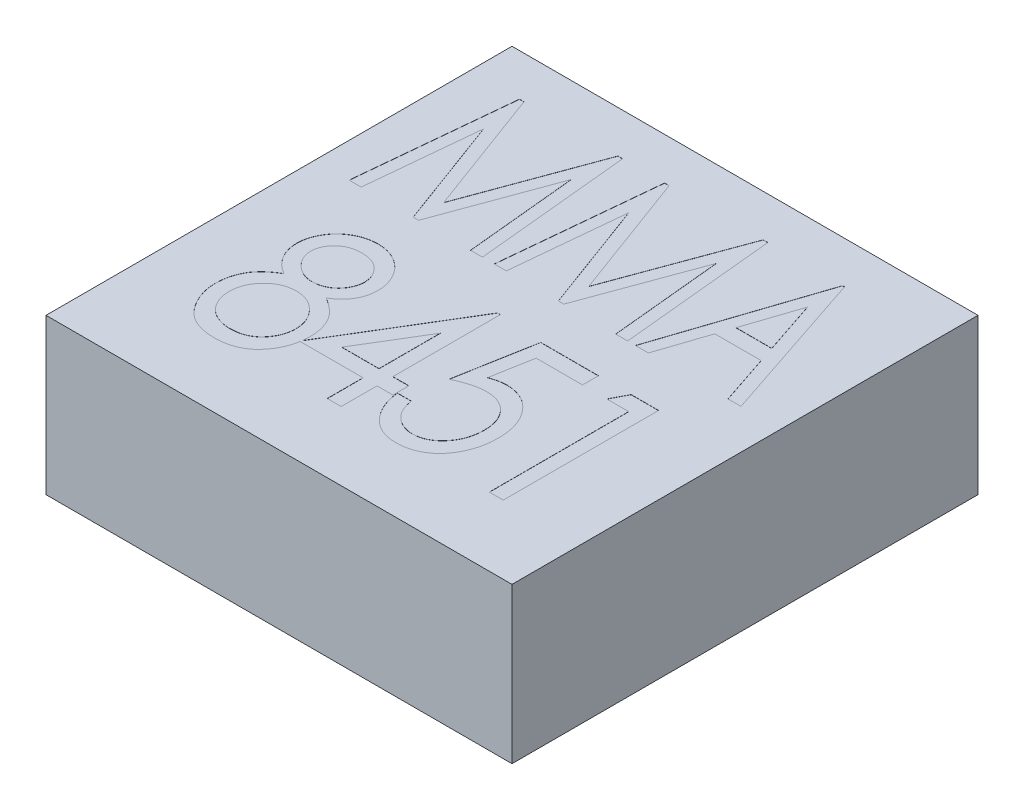
SolidWorks part; units mm, degrees
ref_plane "Piano frontale" through (0, 0, 0) normal (0, 0, 1) x (1, 0, 0)
ref_plane "Piano superiore" through (0, 0, 0) normal (0, 1, 0) x (1, 0, 0)
ref_plane "Piano destro" through (0, 0, 0) normal (1, 0, 0) x (0, 0, -1)
sketch "Schizzo1" plane through (0, 0, 0) normal (0, 1, 0) x (1, 0, 0)
  line L1 (-6.6108, 10.6348) -> (-3.6108, 10.6348)
  line L2 (-6.6108, 10.6348) -> (-6.6108, 7.6348)
  line L3 (-6.6108, 7.6348) -> (-3.6108, 7.6348)
  line L4 (-3.6108, 10.6348) -> (-3.6108, 7.6348)
  dimension "D1" = 3
  dimension "D2" = 3
extrude "Estrusione-Estrusione1" add sketch "Schizzo1" along normal blind 1
sketch "Schizzo2" plane through (0, 1, 0) normal (0, 1, 0) x (1, 0, 0)
  text T0 "MMA\r\n" font "Century Gothic" height 1
extrude "Taglio-Estrusione4" cut sketch "Schizzo2" against normal blind 0.001
sketch "Schizzo3" plane through (0, 1, 0) normal (0, 1, 0) x (1, 0, 0)
  text T0 "8451" font "Century Gothic" height 1
extrude "Taglio-Estrusione5" cut sketch "Schizzo3" against normal blind 0.001
